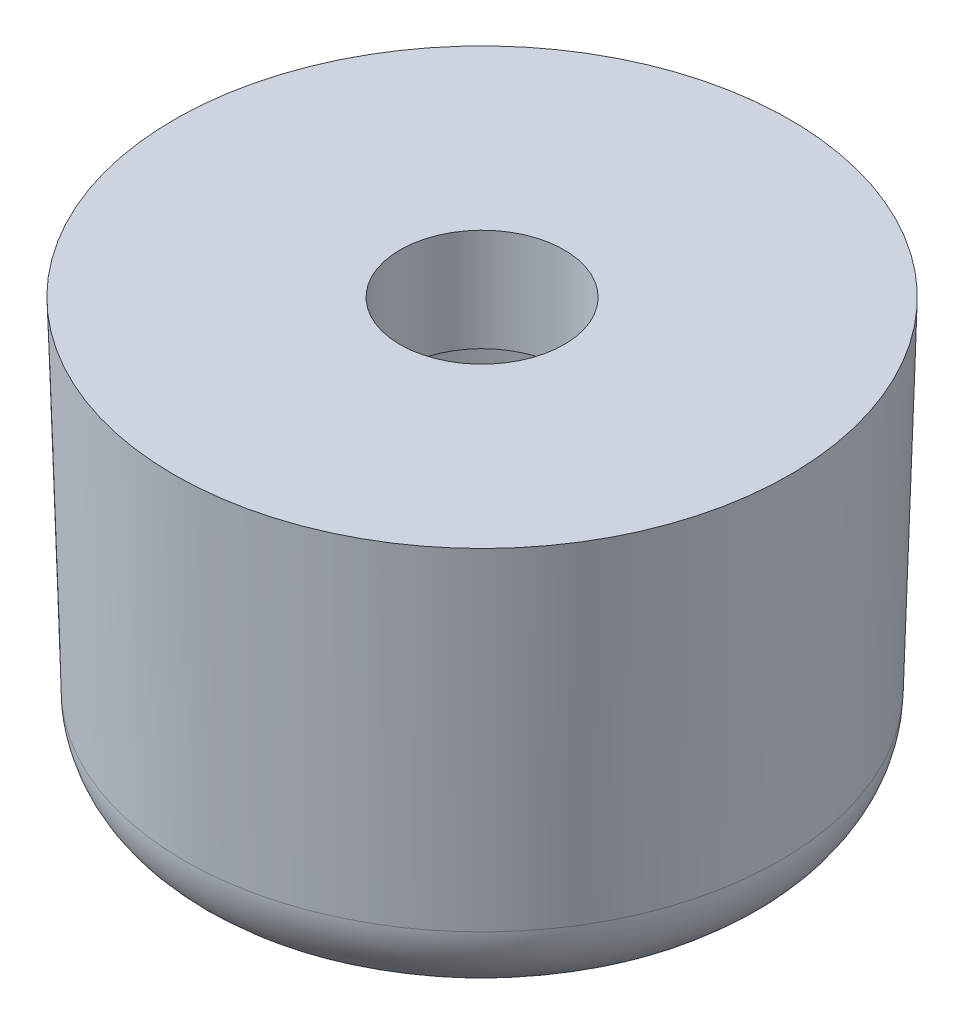
SolidWorks part; units mm, degrees
material "Rubber"
ref_plane "Front Plane" through (0, 0, 0) normal (0, 0, 1) x (1, 0, 0)
ref_plane "Top Plane" through (0, 0, 0) normal (0, 1, 0) x (1, 0, 0)
ref_plane "Right Plane" through (0, 0, 0) normal (1, 0, 0) x (0, 0, -1)
sketch "Sketch1" plane through (0, 0, 0) normal (1, 0, 0) x (0, 0, -1)
  line L0 (0, 6.477) -> (0, 0) construction
  line L1 (1.27, 6.477) -> (4.7625, 6.477)
  line L2 (4.7625, 6.477) -> (4.6082, 1.2292)
  line L4 (3.3422, 0) -> (3.2031, 4.8895)
  line L5 (3.2031, 4.8895) -> (1.27, 4.8895)
  line L6 (1.27, 6.477) -> (1.27, 4.8895)
  arc A0 (4.6082, 1.2292) -> (3.3422, 0) centre (3.3422, 1.2665) cw
  point P7 (4.572, 0)
  dimension "D4" = 1.2665
  dimension "D5" = 1.5875
revolve "Revolve1" add sketch "Sketch1" angle 360 about L0
